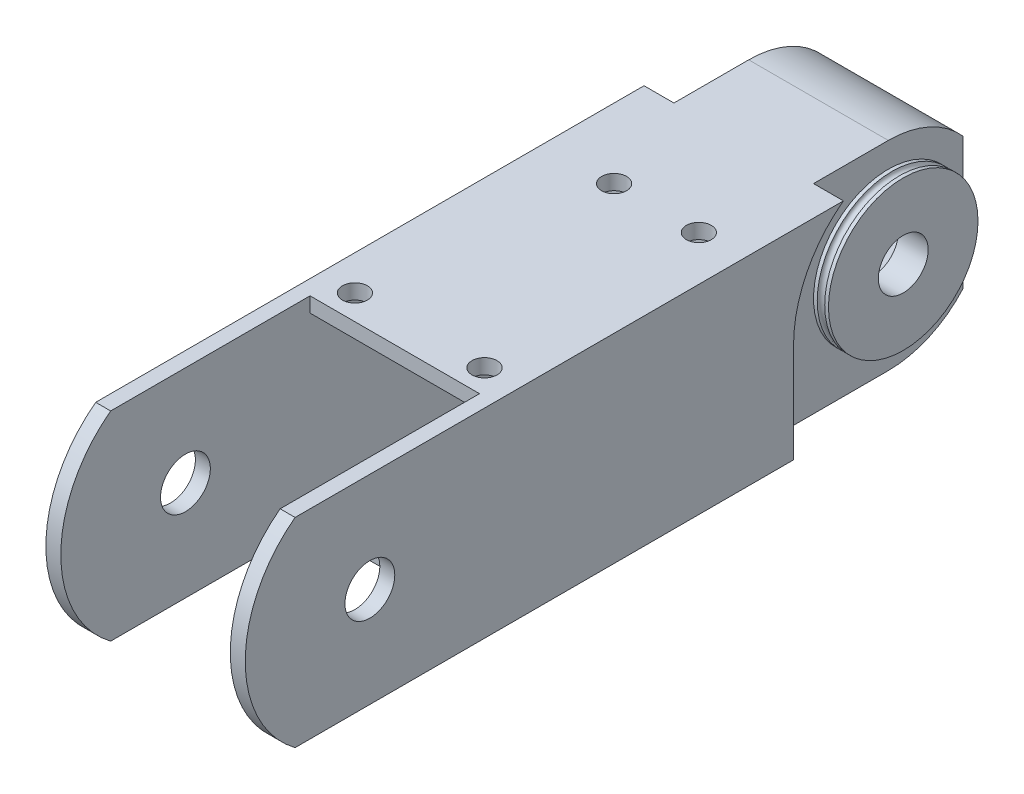
SolidWorks part; units mm, degrees
ref_plane "Alzado" through (0, 0, 0) normal (0, 0, 1) x (1, 0, 0)
ref_plane "Planta" through (0, 0, 0) normal (0, 1, 0) x (1, 0, 0)
ref_plane "Vista lateral" through (0, 0, 0) normal (1, 0, 0) x (0, 0, -1)
sketch "Croquis1" plane through (0, 0, 0) normal (0, 0, 1) x (1, 0, 0)
  line L1 (-20, -20) -> (20, -20)
  line L2 (-20, -20) -> (-20, 20)
  line L3 (-20, 20) -> (20, 20)
  line L4 (20, -20) -> (20, 20)
  line L5 (-20, -20) -> (20, 20) construction
  line L6 (-20, 20) -> (20, -20) construction
  point P0 (0, 0)
  dimension "D1" = 40
  dimension "D2" = 40
extrude "Saliente-Extruir1" add sketch "Croquis1" along normal blind 150
sketch "Croquis2" plane through (0, 0, 150) normal (0, 0, 1) x (1, 0, 0)
  line L0 (20, 20) -> (-20, 20) construction
  line L1 (-17, 20) -> (17, 20)
  line L2 (-17, 20) -> (-17, -20)
  line L3 (-17, -20) -> (17, -20)
  line L4 (17, 20) -> (17, -20)
  line L5 (-20, -20) -> (20, -20) construction
  line L6 (-20, 20) -> (-20, -20) construction
  line L7 (20, -20) -> (20, 20) construction
  dimension "D1" = 3
  dimension "D2" = 3
extrude "Cortar-Extruir1" cut sketch "Croquis2" against normal blind 50
sketch "Croquis3" plane through (20, 0, 0) normal (1, 0, 0) x (0, 0, -1)
  line L0 (-150, -20) -> (0, -20) construction
  line L1 (-150, 20) -> (-140, 20)
  line L2 (-150, 20) -> (-150, 0)
  line L3 (-150, -20) -> (-140, -20)
  line L4 (-150, 20) -> (0, 20) construction
  line L7 (-150, 0) -> (-150, -20)
  arc A0 (-140, 20) -> (-150, 0) centre (-125, 0) ccw
  arc A1 (-150, 0) -> (-140, -20) centre (-125, 0) ccw
  dimension "D1" = 25
  dimension "D2" = 10
extrude "Cortar-Extruir5" cut sketch "Croquis3" against normal through all contours L2 L1 A0 | L7 L3 A1
sketch "Croquis4" plane through (20, 0, 0) normal (1, 0, 0) x (0, 0, -1)
  circle A0 centre (-125, 0) radius 5
  dimension "D1" = 10
extrude "Cortar-Extruir6" cut sketch "Croquis4" against normal through all
sketch "Croquis8" plane through (20, 0, 0) normal (1, 0, 0) x (0, 0, -1)
  line L0 (-140, 20) -> (0, 20) construction
  line L1 (0, -20) -> (0, 20) construction
  line L2 (-140, -20) -> (0, -20) construction
  arc A0 (-15, 20) -> (0, 13.2288) centre (-15, 0) cw
  arc A1 (0, -13.2288) -> (-15, -20) centre (-15, 0) cw
  point P10 (0, 0)
  line M2 (0, 20) -> (-140, 20)
  line M4 (-140, -20) -> (0, -20)
  line M5 (0, -20) -> (0, 20)
  dimension "D1" = 20
  dimension "D3" = 20
  dimension "D2" = 15
  dimension "D4" = 15
extrude "Cortar-Extruir10" cut sketch "Croquis8" against normal through all contours A0 M2 M5 | A1 M5 M4
sketch "Croquis5" plane through (20, 0, 0) normal (1, 0, 0) x (0, 0, -1)
  line L0 (0, -13.2288) -> (0, 13.2288) construction
  circle A0 centre (-15, 0) radius 5
  point P4 (0, 0)
  dimension "D1" = 15
  dimension "D2" = 10
extrude "Cortar-Extruir7" cut sketch "Croquis5" against normal through all
sketch "Croquis6" plane through (20, 0, 0) normal (1, 0, 0) x (0, 0, -1)
  line L0 (-140, -20) -> (-15, -20) construction
  line L1 (-140, 20) -> (-15, 20) construction
  arc A0 (-30, -20) -> (-30, 20) centre (-15, 0) cw
  circle A2 centre (-15, 0) radius 5 construction
  circle M1 centre (-15, 0) radius 5
  line M3 (-15, 20) -> (-140, 20)
  line M5 (-140, -20) -> (-15, -20)
  line M6 (0, -13.2288) -> (0, 13.2288)
  arc M11 (-15, -20) -> (0, -13.2288) centre (-15, 0) ccw
  arc M12 (0, 13.2288) -> (-15, 20) centre (-15, 0) ccw
  dimension "D1" = 25
extrude "Cortar-Extruir8" cut sketch "Croquis6" against normal blind 6 contours A0 M5 M11 M6 M12 M3 M1
sketch "Croquis9" plane through (-20, 0, 0) normal (-1, 0, 0) x (0, 0, 1)
  line L0 (140, 20) -> (15, 20) construction
  line L1 (140, -20) -> (15, -20) construction
  arc A0 (30, 20) -> (30, -20) centre (15, 0) cw
  circle A1 centre (15, 0) radius 5 construction
  circle M1 centre (15, 0) radius 5
  line M3 (0, 13.2288) -> (0, -13.2288)
  arc M4 (0, -13.2288) -> (15, -20) centre (15, 0) ccw
  line M5 (15, -20) -> (140, -20)
  line M7 (140, 20) -> (15, 20)
  arc M8 (15, 20) -> (0, 13.2288) centre (15, 0) ccw
  dimension "D1" = 25
extrude "Cortar-Extruir11" cut sketch "Croquis9" against normal blind 6 contours A0 M7 M8 M3 M4 M5 M1
sketch "Croquis10" plane through (14, 0, 0) normal (1, 0, 0) x (0, 0, -1)
  circle A0 centre (-15, 0) radius 15
  circle A1 centre (-15, 0) radius 5 construction
  circle A2 centre (-15, 0) radius 5
  dimension "D1" = 30
extrude "Saliente-Extruir2" add sketch "Croquis10" along normal blind 3
sketch "Croquis11" plane through (-14, 0, 0) normal (-1, 0, 0) x (0, 0, 1)
  circle A0 centre (15, 0) radius 15
  circle A1 centre (15, 0) radius 5 construction
  circle A2 centre (15, 0) radius 5
  dimension "D1" = 30
extrude "Saliente-Extruir3" add sketch "Croquis11" along normal blind 3
ref_axis "Eje1" through (-18, 0, 15) along (1, 0, 0)
ref_plane "Plano1" through (0, 0, 15) normal (0, 0, 1) x (1, 0, 0)
sketch "Croquis12" plane through (0, 0, 15) normal (0, 0, 1) x (1, 0, 0)
  line L2 (17, 15) -> (14, 15) construction
  line L3 (-14, 15) -> (-17, 15) construction
  circle A0 centre (15.5, 15) radius 0.75
  circle A1 centre (-15.5, 15) radius 0.75
  dimension "D1" = 1.5
  dimension "D2" = 1.5
revolve "Cortar-Revolución1" cut sketch "Croquis12" angle 360 about axis through (-18, 0, 15) along (1, 0, 0)
sketch "Croquis13" plane through (20, 0, 0) normal (1, 0, 0) x (0, 0, -1)
  line L0 (-40, -20) -> (-40, 0)
  line L1 (-140, -20) -> (-30, -20) construction
  arc A0 (-30, 20) -> (-30, -20) centre (-15, 0) ccw construction
  arc M2 (-30, -20) -> (-30, 20) centre (-15, 0) cw
  line M5 (-140, -20) -> (-30, -20)
extrude "Cortar-Extruir12" cut sketch "Croquis13" against normal blind 6 contours L0 M5 M2
sketch "Croquis14" plane through (-20, 0, 0) normal (-1, 0, 0) x (0, 0, 1)
  line L0 (40, -20) -> (40, 0)
  line L1 (140, -20) -> (30, -20) construction
  arc A0 (30, -20) -> (30, 20) centre (15, 0) ccw construction
  arc M2 (30, 20) -> (30, -20) centre (15, 0) cw
  line M3 (30, -20) -> (140, -20)
extrude "Cortar-Extruir13" cut sketch "Croquis14" against normal blind 6 contours L0 M3 M2
sketch "Croquis15" plane through (0, 0, 0) normal (0, 0, -1) x (-1, 0, 0)
  line L0 (14, 13.2288) -> (-14, 13.2288) construction
  line L1 (11, -10.2288) -> (-11, -10.2288)
  line L2 (11, -10.2288) -> (11, 10.2288)
  line L3 (11, 10.2288) -> (-11, 10.2288)
  line L4 (-11, -10.2288) -> (-11, 10.2288)
  line L5 (11, -10.2288) -> (-11, 10.2288) construction
  line L6 (11, 10.2288) -> (-11, -10.2288) construction
  line L7 (-14, -13.2288) -> (-14, 0) construction
  point P0 (0, 0)
  dimension "D1" = 3
  dimension "D2" = 3
extrude "Cortar-Extruir14" cut sketch "Croquis15" against normal through all
sketch "Croquis16" plane through (0, 0, 100) normal (0, 0, 1) x (1, 0, 0)
  line L0 (17, 20) -> (-17, 20) construction
  line L1 (-17, -17) -> (17, -17)
  line L2 (-17, -17) -> (-17, 17)
  line L3 (-17, 17) -> (17, 17)
  line L4 (17, -17) -> (17, 17)
  line L5 (-17, -17) -> (17, 17) construction
  line L6 (-17, 17) -> (17, -17) construction
  line L8 (17, 20) -> (17, -20) construction
  point P0 (0, 0)
  dimension "D1" = 3
extrude "Cortar-Extruir15" cut sketch "Croquis16" against normal blind 55
sketch "Croquis17" plane through (0, 20, 0) normal (0, 1, 0) x (1, 0, 0)
  line L0 (-20, -140) -> (-20, -30) construction
  line L1 (20, -140) -> (20, -30) construction
  line L2 (17, -100) -> (-17, -100) construction
  circle A0 centre (-13, -95) radius 2.5
  circle A1 centre (13, -95) radius 2.5
  dimension "D1" = 5
  dimension "D2" = 5
  dimension "D3" = 7
  dimension "D4" = 7
  dimension "D5" = 5
  dimension "D6" = 5
extrude "Cortar-Extruir16" cut sketch "Croquis17" against normal through all
sketch "Croquis18" plane through (0, 20, 0) normal (0, 1, 0) x (1, 0, 0)
  line L0 (14, -15) -> (14, -30) construction
  line L1 (-14, -30) -> (-14, -15) construction
  line L2 (17, -100) -> (-17, -100) construction
  circle A0 centre (11, -50) radius 2.5
  circle A1 centre (-6, -50) radius 2.5
  dimension "D1" = 5
  dimension "D2" = 5
  dimension "D3" = 3
  dimension "D4" = 8
  dimension "D5" = 50
  dimension "D6" = 50
extrude "Cortar-Extruir17" cut sketch "Croquis18" against normal through all
